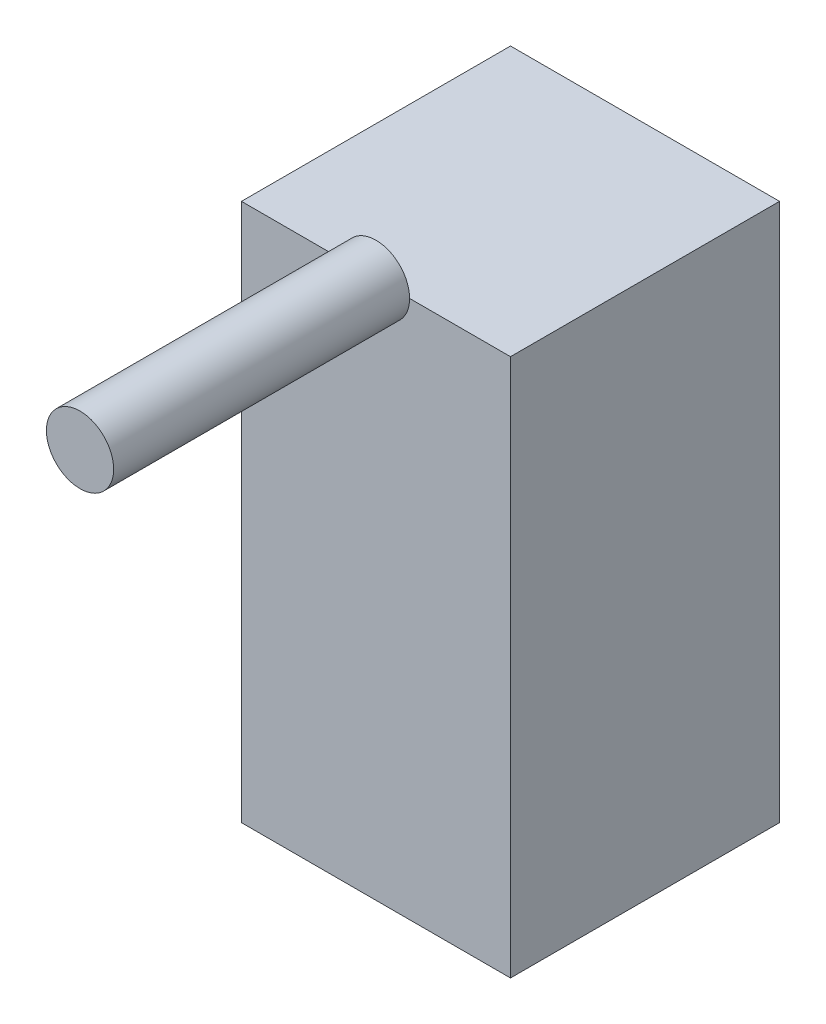
SolidWorks part; units mm, degrees
ref_plane "Front Plane" through (0, 0, 0) normal (0, 0, 1) x (1, 0, 0)
ref_plane "Top Plane" through (0, 0, 0) normal (0, 1, 0) x (1, 0, 0)
ref_plane "Right Plane" through (0, 0, 0) normal (1, 0, 0) x (0, 0, -1)
sketch "Sketch1" plane through (0, 0, 0) normal (0, 1, 0) x (1, 0, 0)
  line L1 (-10, 10) -> (10, 10)
  line L2 (-10, 10) -> (-10, -10)
  line L3 (-10, -10) -> (10, -10)
  line L4 (10, 10) -> (10, -10)
  line L5 (-10, 10) -> (10, -10) construction
  line L6 (-10, -10) -> (10, 10) construction
  point P0 (0, 0)
  dimension "D1" = 20
  dimension "D2" = 20
extrude "Boss-Extrude1" add sketch "Sketch1" along normal blind 40
sketch "Sketch5" plane through (0, 0, 10) normal (0, 0, 1) x (1, 0, 0)
  line L0 (-10, 40) -> (10, 40) construction
  circle A0 centre (0, 40) radius 2.5
  dimension "D1" = 5
extrude "Boss-Extrude4" add sketch "Sketch5" along normal blind 22
